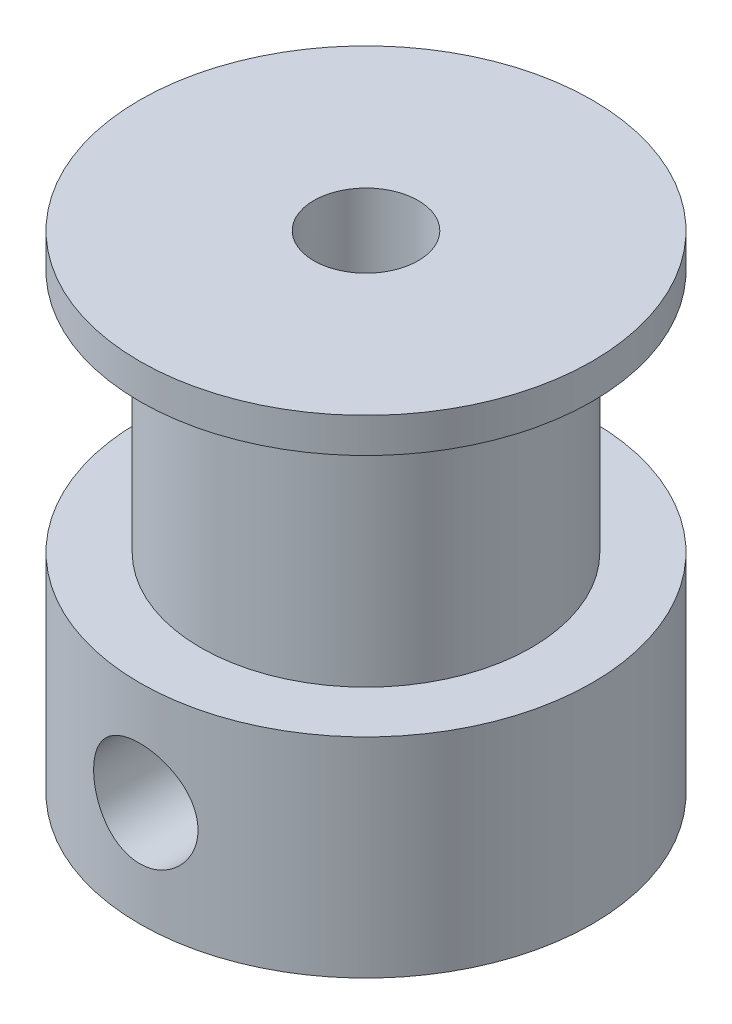
SolidWorks part; units mm, degrees
other "标注1"
sketch "草图4" plane through (6.5, 14, -6.5) normal (0.7486, 0.5007, -0.4346) x (-0.5079, 0.0117, -0.8613)
ref_plane "前视基准面" through (0, 0, 0) normal (0, 0, 1) x (1, 0, 0)
ref_plane "上视基准面" through (0, 0, 0) normal (0, 1, 0) x (1, 0, 0)
ref_plane "右视基准面" through (0, 0, 0) normal (1, 0, 0) x (0, 0, -1)
ref_axis "基准轴1" through (0, 66, 0) along (0, -1, 0)
sketch "草图2" plane through (0, 0, 0) normal (0, 0, 1) x (1, 0, 0)
  line L0 (1.5, 14) -> (6.5, 14)
  line L1 (0, 66) -> (0, -44) construction
  line L2 (6.5, 14) -> (6.5, 13)
  line L3 (6.5, 13) -> (4.75, 13)
  line L4 (4.75, 13) -> (4.75, 6)
  line L5 (4.75, 6) -> (6.5, 6)
  line L6 (6.5, 6) -> (6.5, 0)
  line L7 (6.5, 0) -> (1.5, 0)
  line L9 (1.5, 14) -> (1.5, 0)
  dimension "D1" = 6
  dimension "D2" = 7
  dimension "D3" = 1
  dimension "D4" = 6.5
  dimension "D5" = 4.75
  dimension "D6" = 1.5
revolve "旋转1" add sketch "草图2" angle 360 about axis through (0, 66, 0) along (0, -1, 0)
ref_plane "基准面1" through (0, 0, 6.5) normal (0, 0, 1) x (1, 0, 0)
sketch "草图3" plane through (0, 0, 6.5) normal (0, 0, 1) x (1, 0, 0)
  line L0 (0, 6) -> (0, 0)
  line L1 (6.5, 6) -> (-6.5, 6) construction
  circle A0 centre (0, 3) radius 1.5
  dimension "D1" = 3
extrude "切除-拉伸1" cut sketch "草图3" against normal up to next contours L0 A0 | L0 A0
